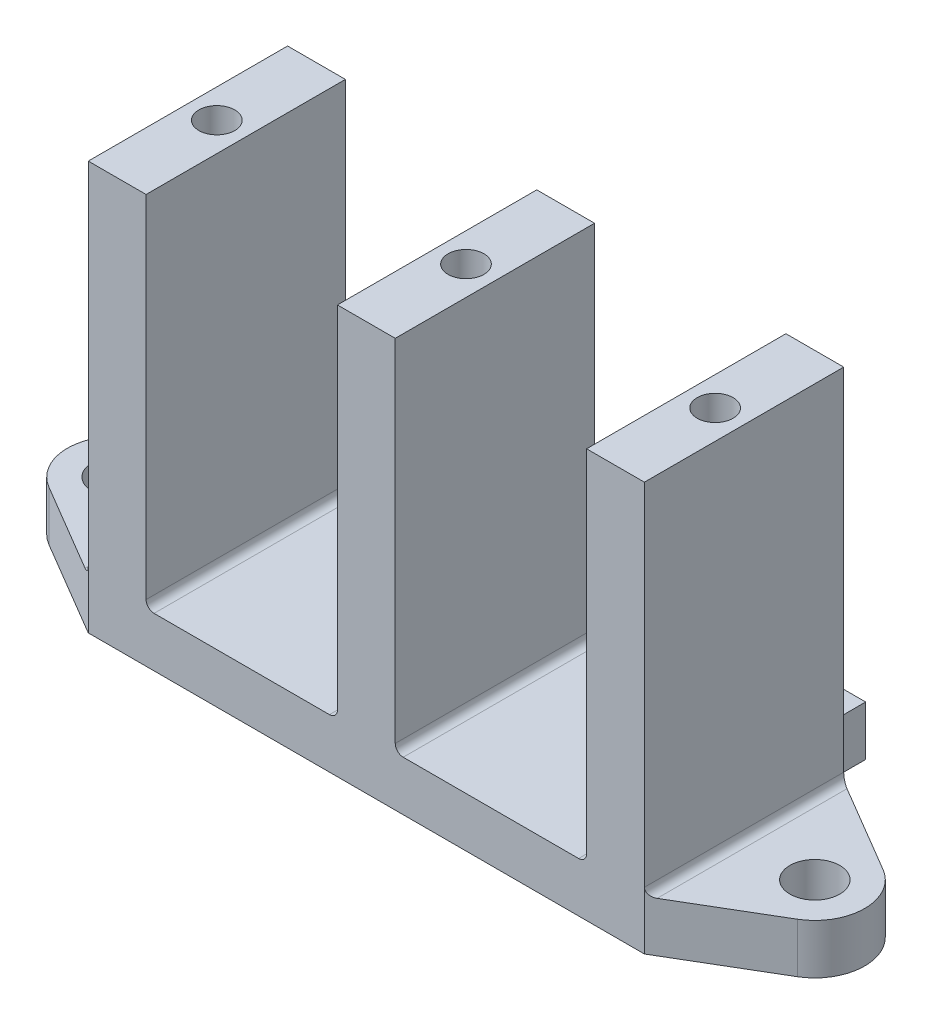
SolidWorks part; units mm, degrees
ref_plane "Front Plane" through (0, 0, 0) normal (0, 0, 1) x (1, 0, 0)
ref_plane "Top Plane" through (0, 0, 0) normal (0, 1, 0) x (1, 0, 0)
ref_plane "Right Plane" through (0, 0, 0) normal (1, 0, 0) x (0, 0, -1)
sketch "Sketch1" plane through (0, 0, 0) normal (0, 1, 0) x (1, 0, 0)
  line L0 (-14.0335, -6.35) -> (-1.8415, -6.35) construction
  line L5 (-1.8415, -6.35) -> (1.8415, -6.35)
  line L6 (-1.8415, -6.35) -> (-1.8415, 6.35)
  line L7 (-1.8415, 6.35) -> (1.8415, 6.35)
  line L8 (1.8415, -6.35) -> (1.8415, 6.35)
  line L9 (-1.8415, -6.35) -> (1.8415, 6.35) construction
  line L10 (-1.8415, 6.35) -> (1.8415, -6.35) construction
  line L11 (-17.7165, -6.35) -> (-14.0335, -6.35)
  line L12 (-17.7165, -6.35) -> (-17.7165, 6.35)
  line L13 (-17.7165, 6.35) -> (-14.0335, 6.35)
  line L14 (-14.0335, -6.35) -> (-14.0335, 6.35)
  line L15 (-17.7165, -6.35) -> (-14.0335, 6.35) construction
  line L16 (-17.7165, 6.35) -> (-14.0335, -6.35) construction
  line L17 (14.0335, -6.35) -> (17.7165, -6.35)
  line L18 (14.0335, -6.35) -> (14.0335, 6.35)
  line L19 (14.0335, 6.35) -> (17.7165, 6.35)
  line L20 (17.7165, -6.35) -> (17.7165, 6.35)
  line L21 (14.0335, -6.35) -> (17.7165, 6.35) construction
  line L22 (14.0335, 6.35) -> (17.7165, -6.35) construction
  line L23 (1.8415, -6.35) -> (14.0335, -6.35) construction
  line L24 (-7.9375, -6.35) -> (-7.9375, -22.225) construction
  line L25 (-7.9375, -22.225) -> (7.9375, -22.225) construction
  line L26 (7.9375, -22.225) -> (7.9375, -6.35) construction
  point P0 (0, 0)
  point P6 (-15.875, 0)
  point P12 (15.875, 0)
  dimension "D1" = 12.192
  dimension "D2" = 15.875
  dimension "D3" = 12.7
extrude "Boss-Extrude1" add sketch "Sketch1" along normal blind 22.86
sketch "Sketch2" plane through (0, 0, 0) normal (0, 1, 0) x (1, 0, 0)
  line L0 (-23.8396, -2.7338) -> (-17.7165, -6.35)
  line L1 (-17.7165, 6.35) -> (17.7165, 6.35)
  line L2 (-17.7165, 6.35) -> (-17.7165, -6.35) construction
  line L3 (-17.7165, -6.35) -> (17.7165, -6.35)
  line L4 (17.7165, 6.35) -> (17.7165, -6.35)
  line L5 (-17.7165, 6.35) -> (17.7165, -6.35) construction
  line L6 (-17.7165, -6.35) -> (17.7165, 6.35) construction
  line L7 (-23.8396, 2.7338) -> (-17.7165, 6.35)
  circle A0 centre (-22.225, 0) radius 1.5875
  arc A1 (-23.8396, -2.7338) -> (-23.8396, 2.7338) centre (-22.225, 0) cw
  point P0 (0, 0)
  dimension "D2" = 3.175
  dimension "D3" = 1.5875
  dimension "D1" = 22.225
extrude "Boss-Extrude2" add sketch "Sketch2" against normal blind 3.175
mirror "Mirror1" about plane through (0, 0, 0) normal (1, 0, 0) of "Boss-Extrude2"
fillet "Fillet1" radius 0.508 6 edges at (-17.7165, 0, 0) (-1.8415, 0, 0) (14.0335, 0, 0) (17.7165, 0, 0) (-14.0335, 0, 0) (1.8415, 0, 0)
sketch "Sketch3" plane through (0, 22.86, 0) normal (0, 1, 0) x (1, 0, 0)
  line L0 (-17.7165, 6.35) -> (-14.0335, -6.35) construction
  line L1 (-1.8415, 6.35) -> (1.8415, -6.35) construction
  line L2 (14.0335, 6.35) -> (17.7165, -6.35) construction
  line L3 (-1.8415, 6.35) -> (-1.8415, -6.35) construction
  circle A0 centre (15.875, 0) radius 1.143
  circle A1 centre (0, 0) radius 1.143
  circle A2 centre (-15.875, 0) radius 1.143
  point P18 (-14.0335, -6.35)
  point P20 (-1.8415, 6.35)
  dimension "D1" = 2.286
extrude "Cut-Extrude1" cut sketch "Sketch3" against normal blind 12.7
sketch "Sketch4" plane through (0, 0, -6.35) normal (0, 0, -1) x (-1, 0, 0)
  line L0 (-14.0335, -3.175) -> (-1.8415, 0) construction
  line L1 (-14.0335, 22.86) -> (-14.0335, 0.508) construction
  line L3 (-1.8415, 22.86) -> (-1.8415, 0.508) construction
  line L4 (17.7165, -3.175) -> (-17.7165, -3.175) construction
  line L5 (-13.5255, 0) -> (-2.3495, 0) construction
  line L6 (-14.0335, 0) -> (-1.8415, 0)
  line L7 (-14.0335, 0) -> (-14.0335, -3.175)
  line L8 (-14.0335, -3.175) -> (-1.8415, -3.175)
  line L9 (-1.8415, 0) -> (-1.8415, -3.175)
  point P4 (-14.0335, 4.8552)
extrude "Boss-Extrude3" add sketch "Sketch4" along normal blind 5.08
fillet "Fillet2" radius 1.5875 2 edges at (1.8415, -1.5875, -6.35) (14.0335, -1.5875, -6.35)
